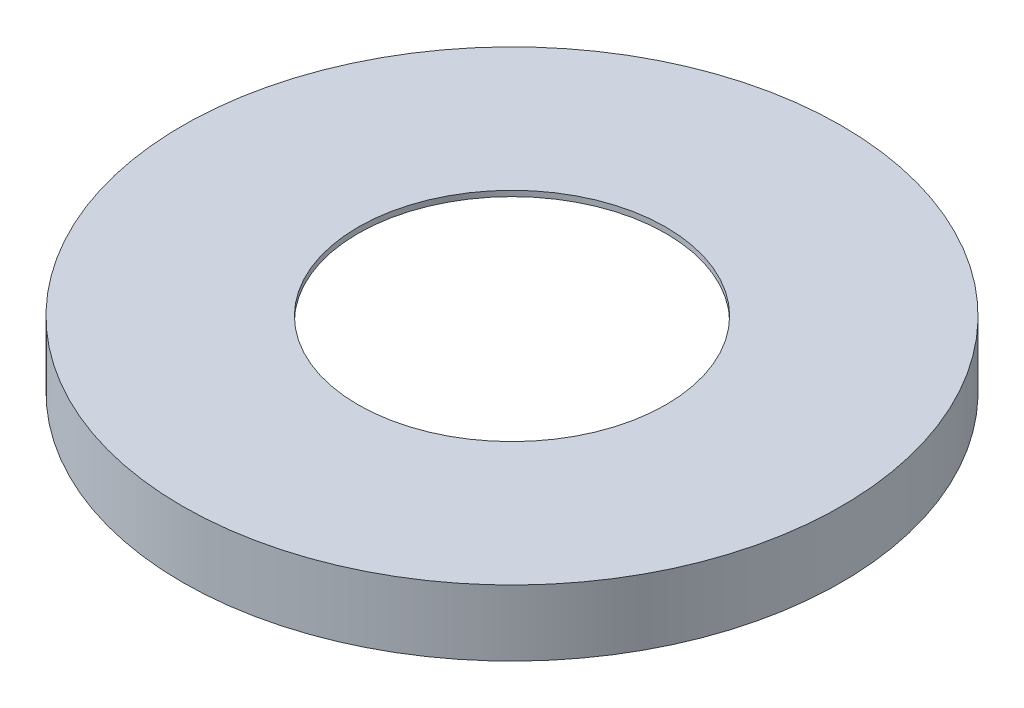
SolidWorks part; units mm, degrees
ref_plane "Front Plane" through (0, 0, 0) normal (0, 0, 1) x (1, 0, 0)
ref_plane "Top Plane" through (0, 0, 0) normal (0, 1, 0) x (1, 0, 0)
ref_plane "Right Plane" through (0, 0, 0) normal (1, 0, 0) x (0, 0, -1)
sketch "Sketch1" plane through (0, 0, 0) normal (0, 1, 0) x (1, 0, 0)
  circle A0 centre (0, 0) radius 30
  circle A1 centre (0, 0) radius 14.01
  dimension "D1" = 60
  dimension "D2" = 28.02
extrude "Boss-Extrude1" add sketch "Sketch1" along normal blind 6
sketch "Sketch2" plane through (0, 0, 0) normal (0, -1, 0) x (1, 0, 0)
  circle A2 centre (0, 0) radius 29
  circle A3 centre (0, 0) radius 29
  dimension "D1" = 1
extrude "Cut-Extrude1" cut sketch "Sketch2" against normal blind 5.5
